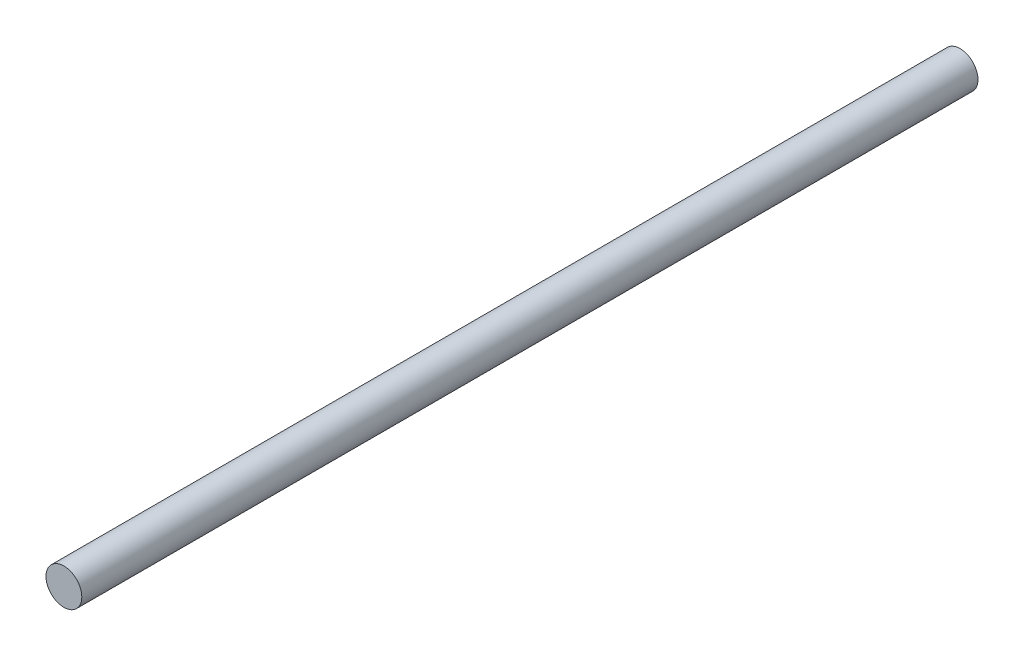
SolidWorks part; units mm, degrees
material "Plain Carbon Steel"
ref_plane "Спереди" through (0, 0, 0) normal (0, 0, 1) x (1, 0, 0)
ref_plane "Сверху" through (0, 0, 0) normal (0, 1, 0) x (1, 0, 0)
ref_plane "Справа" through (0, 0, 0) normal (1, 0, 0) x (0, 0, -1)
sketch "Sketch1" plane through (0, 0, 0) normal (0, 0, 1) x (1, 0, 0)
  circle A0 centre (0, 0) radius 4
  dimension "D1" = 8
extrude "Boss-Extrude1" add sketch "Sketch1" along normal blind 200
